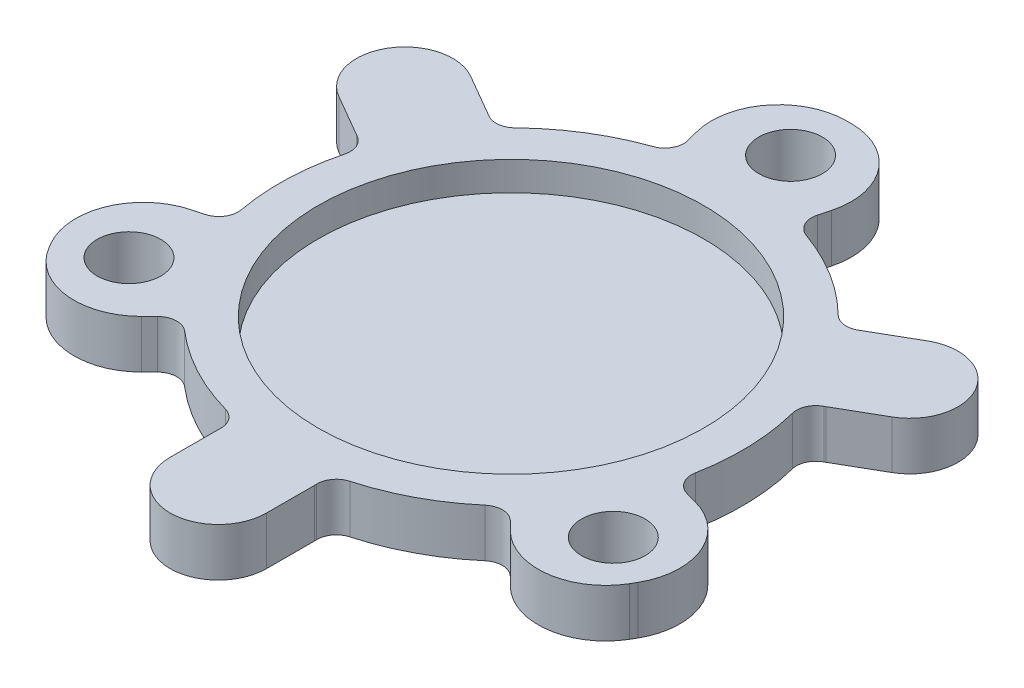
SolidWorks part; units mm, degrees
ref_plane "Спереди" through (0, 0, 0) normal (0, 0, 1) x (1, 0, 0)
ref_plane "Сверху" through (0, 0, 0) normal (0, 1, 0) x (1, 0, 0)
ref_plane "Справа" through (0, 0, 0) normal (1, 0, 0) x (0, 0, -1)
sketch "Sketch1" plane through (0, 0, 0) normal (0, 1, 0) x (1, 0, 0)
  circle A0 centre (0, 0) radius 20
  dimension "D1" = 40
extrude "Boss-Extrude1" add sketch "Sketch1" along normal blind 2
sketch "Sketch2" plane through (0, 0, 0) normal (0, 1, 0) x (1, 0, 0)
  circle A0 centre (0, 0) radius 35
  circle A1 centre (0, 0) radius 20
  circle A2 centre (0, 0) radius 29 construction
  circle A3 centre (0, 29) radius 3.3
  circle A4 centre (25.1147, -14.5) radius 3.3
  circle A5 centre (-25.1147, -14.5) radius 3.3
  point P16 (0, 0)
  dimension "D2" = 58
  dimension "D3" = 40
  dimension "D4" = 70
  dimension "D1" = 3
extrude "Boss-Extrude2" add sketch "Sketch2" along normal blind 5
sketch "Sketch3" plane through (0, 5, 0) normal (0, 1, 0) x (1, 0, 0)
  line L0 (0, 0) -> (-14.9511, 56.1994)
  line L1 (0, 0) -> (-49.3774, -13.1362)
  line L2 (-14.9511, 56.1994) -> (-49.3774, -13.1362)
  line L3 (56.1457, -15.1516) -> (13.3124, 49.3302)
  line L4 (0, 0) -> (13.3124, 49.3302)
  line L5 (0, 0) -> (56.1457, -15.1516)
  line L6 (-41.1945, -41.0477) -> (36.065, -36.1939)
  line L7 (0, 0) -> (36.065, -36.1939)
  line L8 (0, 0) -> (-41.1945, -41.0477)
  circle A0 centre (0, 0) radius 24
  point P12 (0, 0)
  circle M10 centre (0, 0) radius 35
  dimension "D1" = 3
extrude "Cut-Extrude1" cut sketch "Sketch3" against normal blind 10 contours L0 L2 L1 M10 | A0 L0 L1 M10 | L5 L3 L4 M10 | A0 L5 L4 M10 | L8 L6 L7 M10 | A0 L8 L7 M10
fillet "Fillet1" radius 2 6 edges at (16.9402, 2.5, 17.0008) (23.1711, 2.5, 6.253) (6.253, 2.5, -23.1711) (-17.0008, 2.5, 16.9402) (-23.1933, 2.5, 6.1703) (-6.1703, 2.5, -23.1933)
fillet "Fillet2" radius 7 6 edges at (-33.8235, 2.5, 8.9983) (-24.7929, 2.5, 24.7045) (24.7045, 2.5, 24.7929) (33.7912, 2.5, 9.119) (9.119, 2.5, -33.7912) (-8.9983, 2.5, -33.8235)
sketch "Sketch4" plane through (0, 5, 0) normal (0, 1, 0) x (1, 0, 0)
  line L0 (0, 0) -> (-20.7632, 12.0371) construction
  line L1 (-26.2127, 15.1964) -> (-21.887, 12.6886) construction
  line L2 (-23.705, 19.522) -> (-19.3793, 17.0143)
  line L3 (-28.7204, 10.8707) -> (-24.3948, 8.363)
  line L4 (23.7745, 19.4373) -> (19.4399, 16.945)
  line L5 (28.759, 10.7681) -> (24.4245, 8.2758)
  line L6 (26.2668, 15.1027) -> (21.9322, 12.6104) construction
  line L7 (4.9459, -30.308) -> (4.9548, -25.308)
  line L8 (-5.0541, -30.2901) -> (-5.0451, -25.2901)
  line L9 (-0.0541, -30.299) -> (-0.0452, -25.299) construction
  arc A0 (-7.9361, 22.6499) -> (-23.5992, -4.3679) centre (0, 0) ccw construction
  arc A1 (-23.705, 19.522) -> (-28.7204, 10.8707) centre (-26.2127, 15.1964) ccw
  arc A2 (-24.3948, 8.363) -> (-19.3793, 17.0143) centre (-21.887, 12.6886) ccw
  arc A3 (28.759, 10.7681) -> (23.7745, 19.4373) centre (26.2668, 15.1027) ccw
  arc A4 (19.4399, 16.945) -> (24.4245, 8.2758) centre (21.9322, 12.6104) ccw
  arc A5 (-5.0541, -30.2901) -> (4.9459, -30.308) centre (-0.0541, -30.299) ccw
  arc A6 (4.9548, -25.308) -> (-5.0451, -25.2901) centre (-0.0452, -25.299) ccw
  point P8 (-24.0499, 13.9425)
  point P17 (24.0995, 13.8565)
  point P24 (-0.0496, -27.799)
  point P29 (0, 0)
  dimension "D1" = 5
  dimension "D3" = 10
  dimension "D2" = 3
extrude "Boss-Extrude3" add sketch "Sketch4" against normal blind 5
fillet "Fillet3" radius 2 6 edges at (18.0738, 2.5, -15.7905) (22.7394, 2.5, -7.676) (4.638, 2.5, 23.5476) (-4.7221, 2.5, 23.5309) (-22.7118, 2.5, -7.7571) (-18.0173, 2.5, -15.8549)
